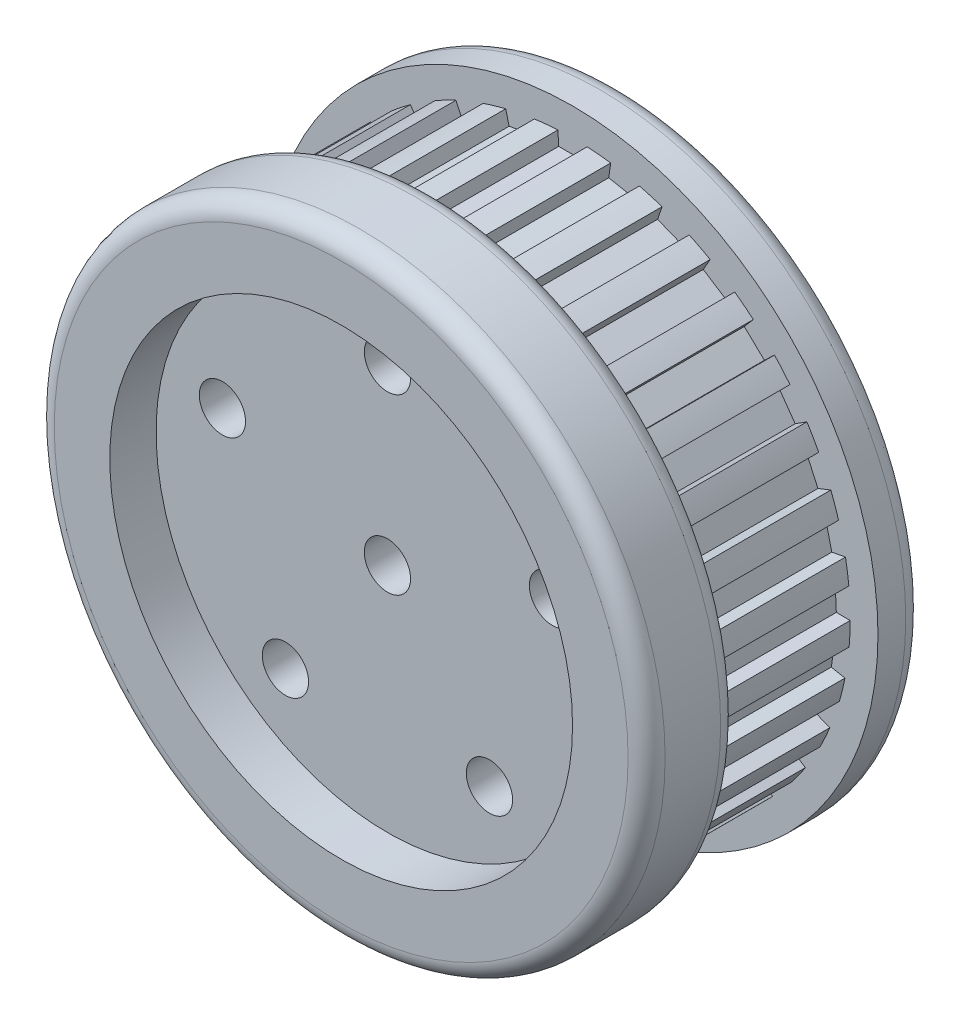
SolidWorks part; units mm, degrees
material "Teak"
ref_plane "Plano frontal" through (0, 0, 0) normal (0, 0, 1) x (1, 0, 0)
ref_plane "Plano superior" through (0, 0, 0) normal (0, 1, 0) x (1, 0, 0)
ref_plane "Plano direito" through (0, 0, 0) normal (1, 0, 0) x (0, 0, -1)
sketch "Sketch1" plane through (0, 0, 0) normal (0, 1, 0) x (1, 0, 0)
  line L0 (0, 0) -> (0, 10)
  line L1 (0, 10) -> (25, 10)
  line L2 (25, 10) -> (25, 25)
  line L3 (25, 25) -> (33, 25)
  line L4 (33, 25) -> (33, 20)
  line L5 (33, 20) -> (30, 20)
  line L7 (30, 5) -> (33, 5)
  line L8 (33, 5) -> (33, -5)
  line L9 (33, -5) -> (25, -5)
  line L10 (25, -5) -> (25, 0)
  line L11 (25, 0) -> (0, 0)
  line L13 (30, 20) -> (30, 5)
  dimension "D1" = 10
  dimension "D2" = 5
  dimension "D3" = 15
  dimension "D4" = 10
  dimension "D5" = 5
  dimension "D6" = 25
  dimension "D7" = 8
  dimension "D8" = 3
revolve "Revolve1" add sketch "Sketch1" angle 360 about L0
sketch "Sketch3" plane through (0, 0, -10) normal (0, 0, -1) x (-1, 0, 0)
  circle A0 centre (0, 0) radius 18.75 construction
  circle A1 centre (0, 0) radius 2.5
  circle A2 centre (0, 18.75) radius 2.5
  circle A3 centre (17.8323, 5.7941) radius 2.5
  circle A4 centre (11.021, -15.1691) radius 2.5
  circle A5 centre (-11.021, -15.1691) radius 2.5
  circle A6 centre (-17.8323, 5.7941) radius 2.5
  point P16 (0, 0)
  dimension "D1" = 37.5
  dimension "D2" = 5
  dimension "D3" = 5
extrude "Cut-Extrude1" cut sketch "Sketch3" against normal through all
sketch "Sketch5" plane through (0, 0, -5) normal (0, 0, -1) x (-1, 0, 0)
  line L1 (-1.5, 28.4605) -> (1.5, 28.4605)
  line L2 (1.5, 28.4605) -> (1.5789, 29.9584)
  line L3 (-1.5, 28.4605) -> (-1.5789, 29.9584)
  circle A0 centre (0, 0) radius 30 construction
  arc A1 (1.5789, 29.9584) -> (-1.5789, 29.9584) centre (0, 0) ccw
  point P7 (0, 28.4605)
  dimension "D2" = 3
  dimension "D1" = 1.5
extrude "Cut-Extrude2" cut sketch "Sketch5" along normal up to surface (15 mm away) up to face at (33, 0, -20)
pattern_circular "CirPattern1" count 33 over 360 about axis through (0, 0, 0) along (0, 0, 1) of "Cut-Extrude2"
fillet "Fillet1" radius 2 5 edges at (33, 0, -25) (33, 0, 5) (33, 0, -5) (25, 0, -10) (25, 0, -25)
